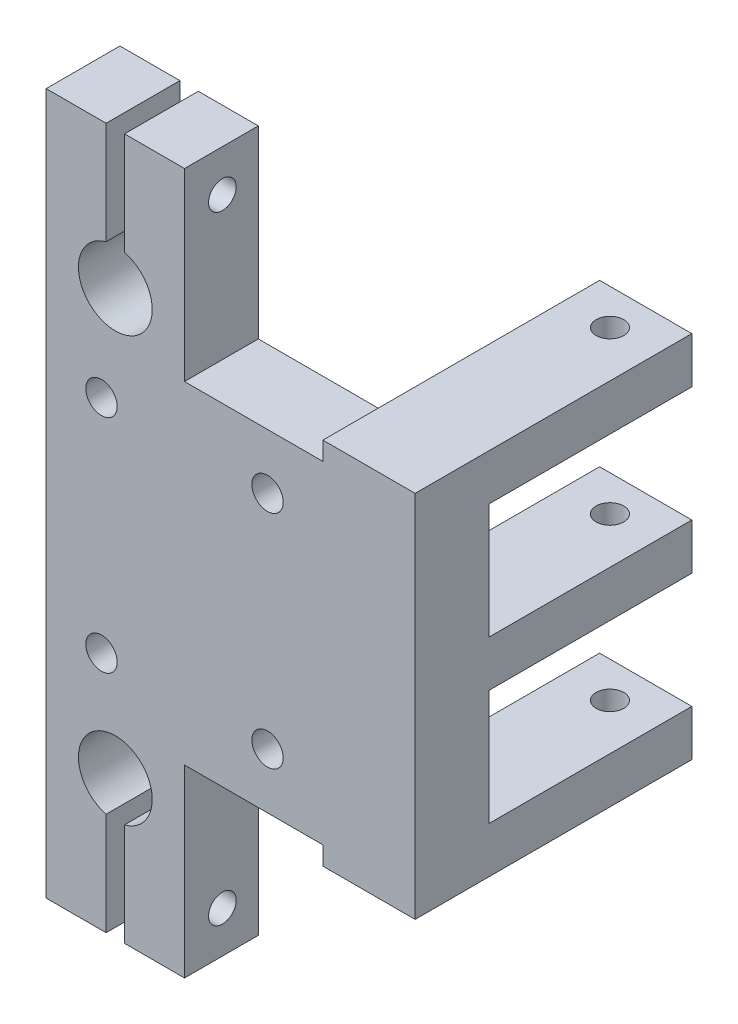
SolidWorks part; units mm, degrees
ref_plane "前视基准面" through (0, 0, 0) normal (0, 0, 1) x (1, 0, 0)
ref_plane "上视基准面" through (0, 0, 0) normal (0, 1, 0) x (1, 0, 0)
ref_plane "右视基准面" through (0, 0, 0) normal (1, 0, 0) x (0, 0, -1)
sketch "草图1" plane through (0, 0, 0) normal (0, 0, 1) x (1, 0, 0)
  line L0 (-18.375, -1.625) -> (11.625, -1.625) construction
  line L1 (-18.375, 16.375) -> (11.625, 16.375)
  line L2 (-18.375, 16.375) -> (-18.375, -19.625)
  line L3 (-18.375, -19.625) -> (11.625, -19.625)
  line L4 (11.625, 16.375) -> (11.625, -19.625)
  line L5 (-3.375, 16.375) -> (-3.375, -19.625) construction
  circle A0 centre (-12.375, 10.375) radius 1.7
  circle A1 centre (-12.375, -13.625) radius 1.7
  circle A2 centre (5.625, -13.625) radius 1.7
  circle A3 centre (5.625, 10.375) radius 1.7
  point P6 (-12.375, -1.625)
  point P10 (-12.375, -1.625)
  dimension "D1" = 36
  dimension "D2" = 30
  dimension "D3" = 6
  dimension "D4" = 24
extrude "凸台-拉伸1" add sketch "草图1" along normal blind 8
sketch "草图2" plane through (0, 0, 0) normal (0, 0, -1) x (-1, 0, 0)
  line L0 (3.375, 16.375) -> (3.375, -19.625) construction
  line L1 (-11.625, 16.375) -> (18.375, 16.375) construction
  line L2 (18.375, -19.625) -> (-11.625, -19.625) construction
  line L3 (-11.625, -1.625) -> (18.375, -1.625) construction
  line L4 (-11.625, -19.625) -> (-11.625, 16.375) construction
  line L5 (18.375, 16.375) -> (18.375, -19.625) construction
  circle A0 centre (12.375, 10.375) radius 3.75
  circle A1 centre (-5.625, 10.375) radius 3.75
  circle A2 centre (12.375, -13.625) radius 3.75
  circle A3 centre (-5.625, -13.625) radius 3.75
extrude "切除-拉伸1" cut sketch "草图2" against normal blind 4.5
sketch "草图3" plane through (0, 0, 8) normal (0, 0, 1) x (1, 0, 0)
  line L0 (-18.375, -1.625) -> (11.625, -1.625) construction
  line L1 (-18.375, 16.375) -> (-3.375, 16.375)
  line L2 (-18.375, 16.375) -> (-18.375, 36.375)
  line L3 (-18.375, 36.375) -> (-3.375, 36.375)
  line L4 (-3.375, 16.375) -> (-3.375, 36.375)
  line L5 (-18.375, 16.375) -> (-18.375, -19.625) construction
  line L6 (11.625, -19.625) -> (11.625, 16.375) construction
  line L7 (-18.375, -39.625) -> (-3.375, -39.625)
  line L8 (-3.375, -19.625) -> (-3.375, -39.625)
  line L9 (-18.375, -19.625) -> (-3.375, -19.625)
  line L10 (-18.375, -19.625) -> (-18.375, -39.625)
  line L11 (-10.875, 36.375) -> (-10.875, -39.625) construction
  line L12 (-10.875, 21.375) -> (-10.875, -24.625)
  circle A0 centre (-10.875, 21.375) radius 4
  circle A1 centre (-10.875, -24.625) radius 4
  point P20 (-10.875, -1.625)
  dimension "D1" = 20
  dimension "D2" = 15
  dimension "D3" = 46
sketch "草图4" plane through (0, 16.375, 0) normal (0, 1, 0) x (1, 0, 0)
  line L0 (11.625, -4) -> (-18.375, -4) construction
  line L1 (11.625, -8) -> (11.625, 0) construction
  line L2 (-18.375, -8) -> (-18.375, 0) construction
extrude "凸台-拉伸4" add sketch "草图3" against normal blind 8
sketch "草图8" plane through (0, 0, 8) normal (0, 0, 1) x (1, 0, 0)
  line L0 (11.625, -19.625) -> (11.625, 16.375) construction
  line L1 (11.625, -1.625) -> (11.625, 18.375) construction
  line L3 (11.625, 18.375) -> (21.625, 18.375)
  line L4 (11.625, 18.375) -> (11.625, -21.625)
  line L5 (11.625, -21.625) -> (21.625, -21.625)
  line L6 (21.625, 18.375) -> (21.625, -21.625)
  dimension "D1" = 20
  dimension "D2" = 40
  dimension "D3" = 10
extrude "凸台-拉伸5" add sketch "草图8" against normal blind 30
sketch "草图10" plane through (11.625, 0, 0) normal (-1, 0, 0) x (0, 0, 1)
  line L0 (-22, -1.625) -> (0, -1.625) construction
  line L1 (-22, 18.375) -> (-22, -21.625) construction
  line L2 (0, -19.625) -> (0, 16.375) construction
  line L3 (0, 0.875) -> (0, -4.125)
  line L4 (0, -16.625) -> (-5, -16.625)
  line L5 (0, 0.875) -> (-5, 0.875)
  line L6 (0, 0.875) -> (0, 13.375)
  line L7 (0, 13.375) -> (-5, 13.375)
  line L8 (-5, 0.875) -> (-5, 13.375)
  line L9 (-5, -4.125) -> (-5, -16.625)
  line L10 (0, -4.125) -> (-5, -4.125)
  line L11 (0, -4.125) -> (0, -16.625)
  line L12 (-5, 0.875) -> (-10, 0.875) construction
  line L13 (-10, -16.625) -> (-22, -16.625)
  line L14 (-10, 0.875) -> (-22, 0.875)
  line L15 (-10, 0.875) -> (-10, 13.375)
  line L16 (-10, 13.375) -> (-22, 13.375)
  line L17 (-22, 0.875) -> (-22, 13.375)
  line L18 (-22, -4.125) -> (-22, -16.625)
  line L19 (-10, -4.125) -> (-22, -4.125)
  line L20 (-10, -4.125) -> (-10, -16.625)
  point P10 (0, -1.625)
  line M15 (-22, 18.375) -> (-22, -21.625)
  line M19 (0, -19.625) -> (0, 16.375)
  dimension "D1" = 5
  dimension "D2" = 12.5
  dimension "D3" = 5
  dimension "D4" = 5
extrude "切除-拉伸4" cut sketch "草图10" against normal blind 30 contours L15 L16 L14 M15 | L8 L5 L7 M19 | L10 L9 L4 M19 | L20 L19 L13 M15
sketch "草图11" plane through (0, 18.375, 0) normal (0, 1, 0) x (1, 0, 0)
  circle A0 centre (16.6218, 18.1233) radius 1.5
extrude "切除-拉伸5" cut sketch "草图11" against normal blind 47 contours A0
sketch "草图12" plane through (0, 0, 0) normal (0, 0, -1) x (-1, 0, 0)
  line L0 (10.875, 36.375) -> (10.875, 25.375) construction
  line L1 (18.375, 36.375) -> (3.375, 36.375) construction
  line L2 (18.375, -39.625) -> (3.375, -39.625) construction
  line L3 (9.875, 49.2961) -> (11.875, 49.2961)
  line L4 (9.875, 49.2961) -> (9.875, 23.4539)
  line L5 (9.875, 23.4539) -> (11.875, 23.4539)
  line L6 (11.875, 49.2961) -> (11.875, 23.4539)
  line L7 (9.875, 49.2961) -> (11.875, 23.4539) construction
  line L8 (9.875, 23.4539) -> (11.875, 49.2961) construction
  line L9 (9.875, -24.2468) -> (11.875, -24.2468)
  line L10 (9.875, -24.2468) -> (9.875, -55.0032)
  line L11 (9.875, -55.0032) -> (11.875, -55.0032)
  line L12 (11.875, -24.2468) -> (11.875, -55.0032)
  line L13 (9.875, -24.2468) -> (11.875, -55.0032) construction
  line L14 (9.875, -55.0032) -> (11.875, -24.2468) construction
  circle A0 centre (10.875, 21.375) radius 4 construction
  point P11 (10.875, -39.625)
  dimension "D1" = 2
  dimension "D2" = 2
extrude "切除-拉伸6" cut sketch "草图12" against normal blind 10
sketch "草图13" plane through (-18.375, 0, 0) normal (-1, 0, 0) x (0, 0, 1)
  line L0 (8, -1.625) -> (0, -1.625) construction
  line L1 (8, 36.375) -> (8, -39.625) construction
  line L2 (0, 36.375) -> (0, -39.625) construction
  circle A0 centre (3.8925, 31.8681) radius 1.5
  circle A1 centre (3.8925, -35.1181) radius 1.5
extrude "切除-拉伸7" cut sketch "草图13" against normal blind 40
sketch "草图14" plane through (21.625, 0, 0) normal (1, 0, 0) x (0, 0, -1)
  line L0 (5, 13.375) -> (10, 13.375)
  line L1 (10, 13.375) -> (10, 0.875)
  line L2 (10, 0.875) -> (5, 0.875)
  line L3 (5, 0.875) -> (5, 13.375)
  line L4 (5, -4.125) -> (10, -4.125)
  line L5 (10, -16.625) -> (10, -4.125) construction
  line L6 (10, -4.125) -> (10, -16.625)
  line L7 (10, -16.625) -> (5, -16.625)
  line L8 (5, -16.625) -> (5, -4.125)
extrude "切除-拉伸8" cut sketch "草图14" against normal blind 10
